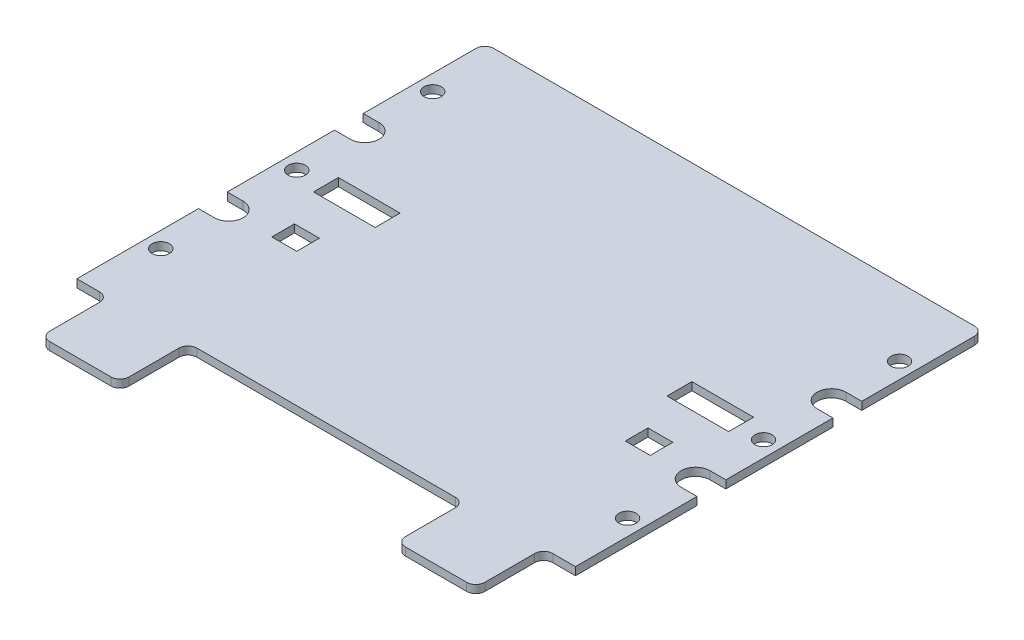
SolidWorks part; units mm, degrees
ref_plane "Front Plane" through (0, 0, 0) normal (0, 0, 1) x (1, 0, 0)
ref_plane "Top Plane" through (0, 0, 0) normal (0, 1, 0) x (1, 0, 0)
ref_plane "Right Plane" through (0, 0, 0) normal (1, 0, 0) x (0, 0, -1)
sketch "Sketch1" plane through (0, 0, 0) normal (0, 1, 0) x (1, 0, 0)
  line L0 (0, 0) -> (5, 0)
  line L1 (5, 0) -> (7, 0) construction
  line L2 (0, 0) -> (110, 0) construction
  line L3 (7, 0) -> (7, -2) construction
  line L4 (5, 0) -> (7, -2) construction
  line L5 (0, 90) -> (110, 90) construction
  line L6 (0, 90) -> (0, 0) construction
  line L7 (0, 0) -> (110, 0) construction
  line L8 (110, 90) -> (110, 0) construction
  line L9 (7, -2) -> (7, -13)
  line L10 (7, -13) -> (9, -13) construction
  line L11 (9, -13) -> (9, -15) construction
  line L12 (110, 0) -> (110, 90) construction
  line L13 (110, 90) -> (0, 90) construction
  line L14 (0, 90) -> (0, 0) construction
  line L15 (9, -15) -> (22.5, -15)
  line L16 (22.5, -15) -> (22.5, -13) construction
  line L17 (22.5, -13) -> (24.5, -13) construction
  line L18 (24.5, -13) -> (24.5, -2)
  line L19 (24.5, -2) -> (24.5, 0) construction
  line L20 (24.5, 0) -> (26.5, 0) construction
  line L21 (26.5, 0) -> (24.5, -2) construction
  line L22 (24.5, -13) -> (22.5, -15) construction
  line L23 (7, -13) -> (9, -15) construction
  line L24 (110, 0) -> (105, 0)
  line L25 (105, 0) -> (103, 0) construction
  line L26 (103, 0) -> (103, -2) construction
  line L27 (103, -2) -> (103, -13)
  line L28 (103, -13) -> (101, -13) construction
  line L29 (101, -13) -> (101, -15) construction
  line L30 (101, -15) -> (87.5, -15)
  line L31 (87.5, -15) -> (87.5, -13) construction
  line L32 (87.5, -13) -> (85.5, -13) construction
  line L33 (85.5, -13) -> (85.5, -2)
  line L34 (85.5, -2) -> (85.5, 0) construction
  line L35 (85.5, 0) -> (83.5, 0) construction
  line L36 (83.5, 0) -> (26.5, 0)
  line L37 (83.5, 0) -> (85.5, -2) construction
  line L38 (103, -2) -> (105, 0) construction
  line L39 (103, -13) -> (101, -15) construction
  line L40 (85.5, -13) -> (87.5, -15) construction
  line L41 (0, 0) -> (0, 88)
  line L42 (0, 88) -> (2, 90) construction
  line L43 (2, 90) -> (108, 90)
  line L44 (108, 90) -> (110, 88) construction
  line L45 (110, 88) -> (110, 0)
  arc A0 (0, 88) -> (2, 90) centre (2, 88) cw
  arc A1 (108, 90) -> (110, 88) centre (108, 88) cw
  arc A2 (5, 0) -> (7, -2) centre (5, -2) cw
  arc A3 (24.5, -2) -> (26.5, 0) centre (26.5, -2) cw
  arc A4 (24.5, -13) -> (22.5, -15) centre (22.5, -13) cw
  arc A5 (7, -13) -> (9, -15) centre (9, -13) ccw
  arc A6 (85.5, -13) -> (87.5, -15) centre (87.5, -13) ccw
  arc A7 (101, -15) -> (103, -13) centre (101, -13) ccw
  arc A8 (103, -2) -> (105, 0) centre (105, -2) cw
  arc A9 (83.5, 0) -> (85.5, -2) centre (83.5, -2) cw
extrude "FR4" add sketch "Sketch1" along normal blind 1.7526
ref_plane "center-of-slot" through (0, 0.8763, 0) normal (0, -1, 0) x (-1, 0, 0)
sketch "Sketch6" plane through (0, 1.7526, 0) normal (0, 1, 0) x (1, 0, 0)
  line L0 (19, 34.5) -> (13.5, 34.5)
  line L1 (97, 34.5) -> (91.5, 34.5)
  line L2 (97, 34.5) -> (97, 29.5)
  line L3 (97, 29.5) -> (91.5, 29.5)
  line L4 (91.5, 34.5) -> (91.5, 29.5)
  line L5 (19, 34.5) -> (19, 29.5)
  line L6 (19, 29.5) -> (13.5, 29.5)
  line L7 (13.5, 34.5) -> (13.5, 29.5)
  line L8 (101.1, 42.7) -> (87.5, 42.7)
  line L9 (101.1, 42.7) -> (101.1, 48.2)
  line L10 (101.1, 48.2) -> (87.5, 48.2)
  line L11 (87.5, 42.7) -> (87.5, 48.2)
  line L29 (23.1, 42.7) -> (9.5, 42.7)
  line L30 (23.1, 42.7) -> (23.1, 48.2)
  line L31 (23.1, 48.2) -> (9.5, 48.2)
  line L32 (9.5, 42.7) -> (9.5, 48.2)
  dimension "D1" = 2
extrude "fiber-transceiver-slots" cut sketch "Sketch6" against normal through all
sketch "Sketch7" plane through (0, 1.7526, 0) normal (0, 1, 0) x (1, 0, 0)
  circle A0 centre (3.5, 15) radius 1.905
  circle A1 centre (106.5, 15) radius 1.905
  circle A2 centre (106.5, 30) radius 1.905
  circle A3 centre (106.5, 45) radius 1.905
  circle A4 centre (106.5, 60) radius 1.905
  circle A5 centre (106.5, 75) radius 1.905
  circle A6 centre (3.5, 30) radius 1.905
  circle A7 centre (3.5, 45) radius 1.905
  circle A8 centre (3.5, 60) radius 1.905
  circle A9 centre (3.5, 75) radius 1.905
  dimension "D1" = 2
  dimension "D2" = 5
extrude "Cut-Extrude1" cut sketch "Sketch7" against normal through all
sketch "Sketch8" plane through (0, 1.7526, 0) normal (0, 1, 0) x (1, 0, 0)
  circle A0 centre (3.5, 30) radius 3.175
  circle A1 centre (3.5, 60) radius 3.175
  circle A2 centre (106.5, 60) radius 3.175
  circle A3 centre (106.5, 30) radius 3.175
extrude "Cut-Extrude2" cut sketch "Sketch8" against normal through all
sketch "Sketch9" plane through (0, 1.7526, 0) normal (0, 1, 0) x (1, 0, 0)
  line L0 (0, 63.175) -> (3.5, 63.175)
  line L1 (0, 88) -> (0, 0) construction
  line L2 (3.5, 56.825) -> (0, 56.825)
  line L3 (0, 56.825) -> (0, 63.175)
  line L4 (0, 33.175) -> (3.5, 33.175)
  line L5 (3.5, 26.825) -> (0, 26.825)
  line L6 (0, 26.825) -> (0, 33.175)
  line L7 (110, 63.175) -> (106.5, 63.175)
  line L8 (110, 0) -> (110, 88) construction
  line L9 (106.5, 56.825) -> (110, 56.825)
  line L10 (110, 56.825) -> (110, 63.175)
  line L11 (110, 33.175) -> (106.5, 33.175)
  line L12 (106.5, 26.825) -> (110, 26.825)
  line L13 (110, 26.825) -> (110, 33.175)
  circle A0 centre (3.5, 60) radius 3.175 construction
  arc A1 (3.5, 63.175) -> (3.5, 56.825) centre (3.5, 60) cw
  circle A2 centre (3.5, 30) radius 3.175 construction
  arc A3 (3.5, 33.175) -> (3.5, 26.825) centre (3.5, 30) cw
  circle A4 centre (106.5, 60) radius 3.175 construction
  arc A5 (106.5, 63.175) -> (106.5, 56.825) centre (106.5, 60) ccw
  circle A6 centre (106.5, 30) radius 3.175 construction
  arc A7 (106.5, 33.175) -> (106.5, 26.825) centre (106.5, 30) ccw
extrude "Cut-Extrude3" cut sketch "Sketch9" against normal through all
